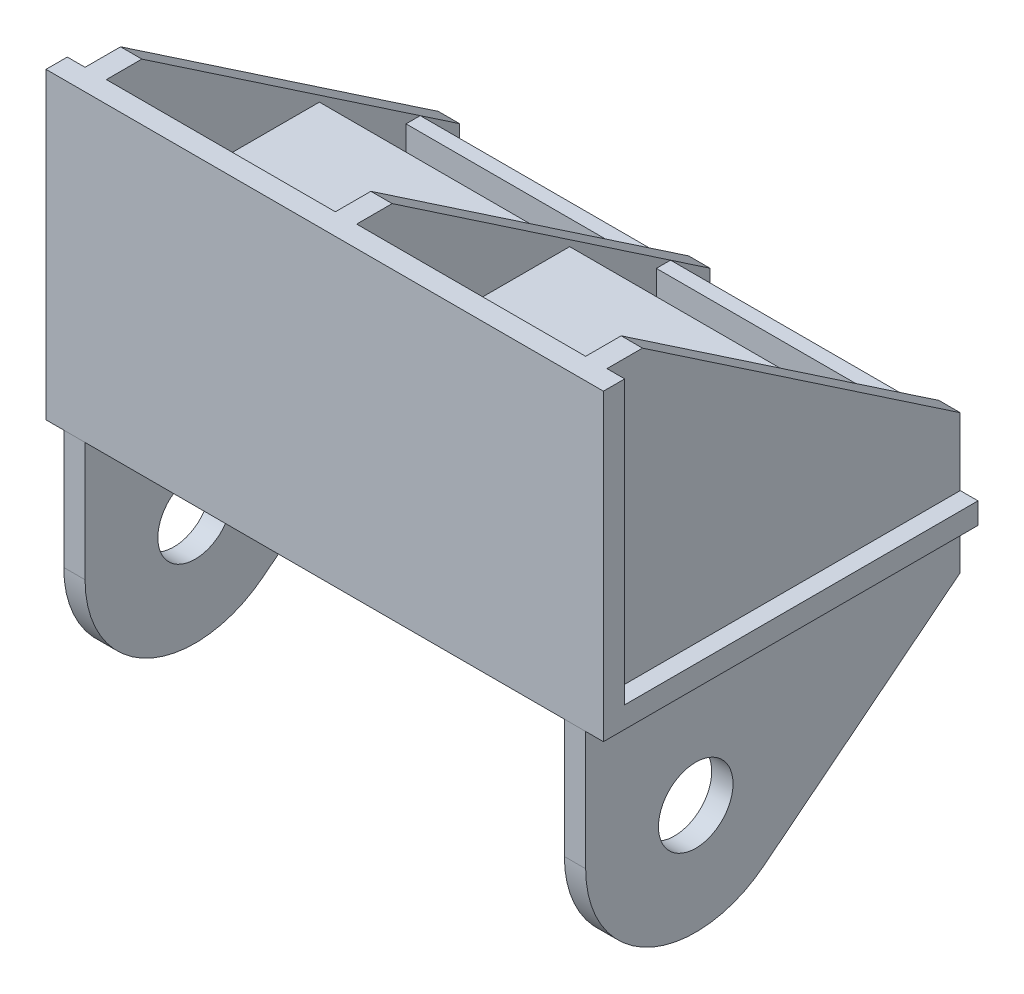
SolidWorks part; units mm, degrees
ref_plane "前视基准面" through (0, 0, 0) normal (0, 0, 1) x (1, 0, 0)
ref_plane "上视基准面" through (0, 0, 0) normal (0, 1, 0) x (1, 0, 0)
ref_plane "右视基准面" through (0, 0, 0) normal (1, 0, 0) x (0, 0, -1)
sketch "草图7" plane through (0, 0, 0) normal (0, 1, 0) x (1, 0, 0)
  line L0 (-1000, 0) -> (49000, 0) construction
  line L1 (-157, 105.5) -> (157, 105.5)
  line L2 (-157, 105.5) -> (-157, -105.5)
  line L3 (-157, -105.5) -> (157, -105.5)
  line L4 (157, 105.5) -> (157, -105.5)
  line L5 (0, -1000) -> (0, 49000) construction
  dimension "D1" = 314
  dimension "D2" = 211
extrude "凸台-拉伸7" add sketch "草图7" along normal blind 12
sketch "草图8" plane through (157, 0, 0) normal (1, 0, 0) x (0, 0, -1)
  line L0 (105.5, 12) -> (105.5, 0) construction
  line L1 (-105.5, 0) -> (105.5, 0)
  line L2 (-105.5, 0) -> (-105.5, -150)
  line L3 (-105.5, -150) -> (105.5, -150)
  line L4 (105.5, 0) -> (105.5, -150)
  dimension "D1" = 150
extrude "凸台-拉伸8" add sketch "草图8" against normal blind 314 separate body
sketch "草图9" plane through (157, 0, 0) normal (1, 0, 0) x (0, 0, -1)
  line L0 (105.5, -28) -> (-4.9843, -115.5854)
  line L1 (105.5, -150) -> (105.5, 0) construction
  line L2 (-105.5, 0) -> (-105.5, -150) construction
  line L3 (105.5, 0) -> (-105.5, 0) construction
  line L4 (-105.5, 0) -> (105.5, 0) construction
  line L5 (-105.5, -67) -> (-105.5, -150)
  line L6 (-105.5, -150) -> (105.5, -150)
  line L7 (105.5, -150) -> (105.5, -28)
  arc A0 (-4.9843, -115.5854) -> (-105.5, -67) centre (-43.5, -67) cw
  circle A1 centre (-43.5, -67) radius 21
  dimension "D3" = 62
  dimension "D5" = 42
  dimension "D1" = 62
  dimension "D2" = 67
  dimension "D4" = 28
extrude "切除-拉伸1" cut sketch "草图9" against normal through all
sketch "草图10" plane through (0, 0, 0) normal (0, 1, 0) x (1, 0, 0)
  line L0 (157, 105.5) -> (-157, 105.5) construction
  line L1 (-135, 105.5) -> (135, 105.5)
  line L2 (-135, 105.5) -> (-135, -105.5)
  line L3 (-135, -105.5) -> (135, -105.5)
  line L4 (135, 105.5) -> (135, -105.5)
  line L5 (-157, -105.5) -> (157, -105.5) construction
  line L8 (-157, 105.5) -> (157, 105.5) construction
  line L9 (-157, -105.5) -> (-147, -105.5)
  line L10 (-157, -105.5) -> (-157, 105.5)
  line L11 (-157, 105.5) -> (-147, 105.5)
  line L12 (-147, -105.5) -> (-147, 105.5)
  line L14 (157, -105.5) -> (147, -105.5)
  line L15 (157, -105.5) -> (157, 105.5)
  line L16 (157, 105.5) -> (147, 105.5)
  line L17 (147, -105.5) -> (147, 105.5)
  dimension "D1" = 135
  dimension "D2" = 135
  dimension "D3" = 12
  dimension "D4" = 12
extrude "切除-拉伸2" cut sketch "草图10" against normal through all
sketch "草图11" plane through (0, 12, 0) normal (0, 1, 0) x (1, 0, 0)
  line L0 (157, -105.5) -> (157, 105.5) construction
  line L1 (-157, -105.5) -> (157, -105.5)
  line L2 (-157, -105.5) -> (-157, -93.5)
  line L3 (-157, -93.5) -> (157, -93.5)
  line L4 (157, -105.5) -> (157, -93.5)
  dimension "D1" = 12
extrude "凸台-拉伸9" add sketch "草图11" along normal blind 159
sketch "草图13" plane through (0, 12, 0) normal (0, 1, 0) x (1, 0, 0)
  line L0 (157, 105.5) -> (-157, 105.5) construction
  line L1 (-6, 105.5) -> (6, 105.5)
  line L2 (-6, 105.5) -> (-6, -93.5)
  line L3 (-6, -93.5) -> (6, -93.5)
  line L4 (6, 105.5) -> (6, -93.5)
  line L5 (157, -93.5) -> (-157, -93.5) construction
  dimension "D1" = 6
  dimension "D2" = 6
extrude "凸台-拉伸11" add sketch "草图13" along normal blind 159
pattern_linear "阵列(线性)2" count 2 spacing 141 along (-1, 0, 0) of "凸台-拉伸11"
pattern_linear "阵列(线性)3" count 2 spacing 141 along (1, 0, 0) of "凸台-拉伸11"
sketch "草图14" plane through (157, 0, 0) normal (1, 0, 0) x (0, 0, -1)
  line L0 (-73.5, 171) -> (105.5, 50)
  line L1 (-105.5, 171) -> (-93.5, 171) construction
  line L2 (105.5, 12) -> (105.5, 0) construction
  line L3 (105.5, 50) -> (105.5, 171)
  line L4 (105.5, 171) -> (-73.5, 171)
  line L5 (-105.5, 171) -> (-105.5, 0) construction
  line L6 (-105.5, 0) -> (105.5, 0) construction
  dimension "D1" = 32
  dimension "D2" = 50
extrude "切除-拉伸3" cut sketch "草图14" against normal through all
sketch "草图15" plane through (-135, 0, 0) normal (1, 0, 0) x (0, 0, -1)
  line L0 (-73.5, 171) -> (105.5, 50) construction
  line L1 (75.3099, 12) -> (83.3099, 12)
  line L2 (75.3099, 12) -> (75.3099, 65)
  line L3 (75.3099, 65) -> (83.3099, 65)
  line L4 (83.3099, 12) -> (83.3099, 65)
  line L6 (-93.5, 12) -> (105.5, 12) construction
  dimension "D1" = 8
  dimension "D2" = 53
extrude "凸台-拉伸12" add sketch "草图15" along normal blind 129
mirror "镜向1" about plane through (0, 0, 0) normal (1, 0, 0) of "凸台-拉伸12"
sketch "草图16" plane through (0, 0, 93.5) normal (0, 0, -1) x (-1, 0, 0)
  line L0 (-135, 171) -> (-135, 12) construction
  line L1 (-135, 100) -> (-6, 100)
  line L2 (-135, 100) -> (-135, 92)
  line L3 (-135, 92) -> (-6, 92)
  line L4 (-6, 100) -> (-6, 92)
  line L6 (6, 171) -> (6, 12) construction
  line L7 (6, 100) -> (135, 100)
  line L8 (6, 100) -> (6, 92)
  line L9 (6, 92) -> (135, 92)
  line L10 (135, 100) -> (135, 92)
  line L12 (-6, 171) -> (-6, 12) construction
  line L13 (135, 65) -> (135, 171) construction
  line L14 (-1147, 96) -> (48853, 96) construction
  line L16 (-135, 171) -> (-6, 171) construction
  dimension "D1" = 8
  dimension "D2" = 75
extrude "凸台-拉伸13" add sketch "草图16" along normal blind 120
